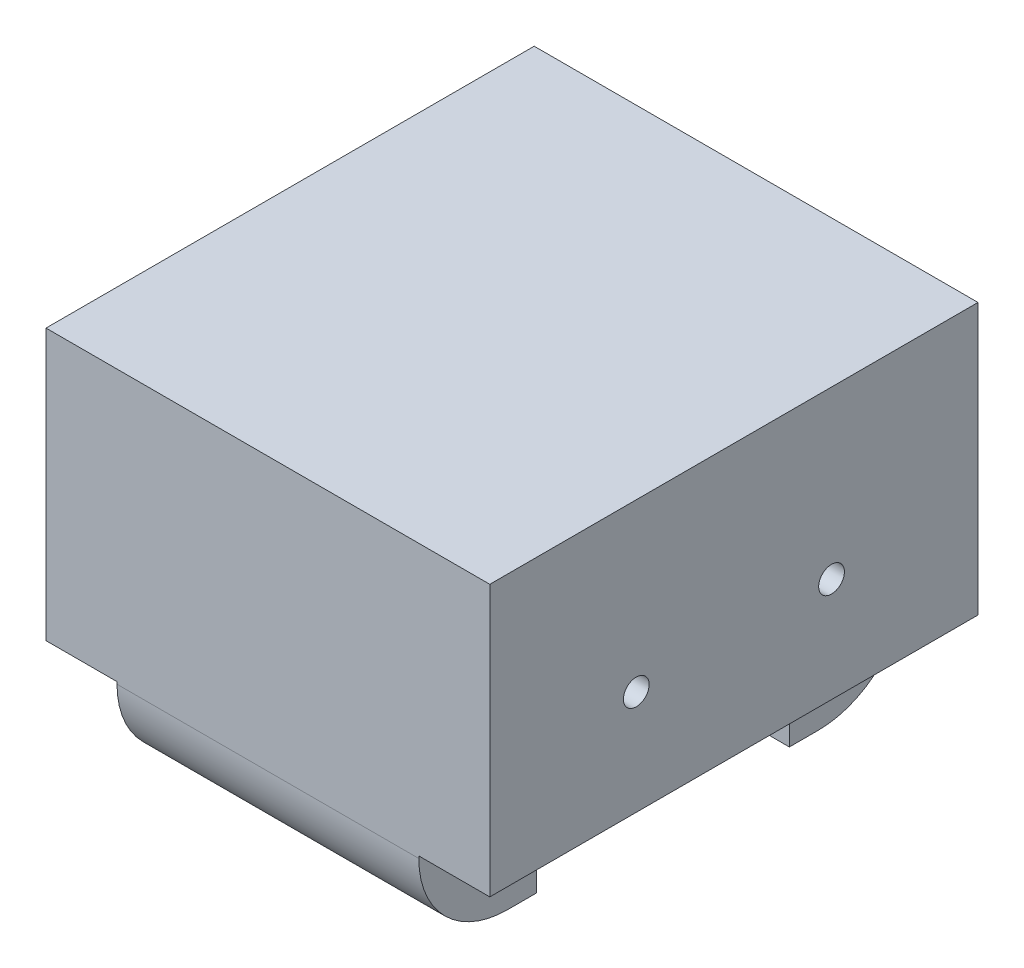
SolidWorks part; units mm, degrees
ref_plane "Front Plane" through (0, 0, 0) normal (0, 0, 1) x (1, 0, 0)
ref_plane "Top Plane" through (0, 0, 0) normal (0, 1, 0) x (1, 0, 0)
ref_plane "Right Plane" through (0, 0, 0) normal (1, 0, 0) x (0, 0, -1)
sketch "Sketch1" plane through (0, 0, 0) normal (0, 0, 1) x (1, 0, 0)
  line L1 (-25, 0) -> (25, 0)
  line L2 (-25, 0) -> (-25, -170)
  line L3 (-25, -170) -> (25, -170)
  line L4 (25, 0) -> (25, -170)
  dimension "D1" = 170
  dimension "D2" = 50
extrude "Boss-Extrude1" add sketch "Sketch1" against normal blind 55
sketch "Sketch2" plane through (0, 0, 0) normal (0, 0, 1) x (1, 0, 0)
  line L0 (25, 0) -> (-25, 0) construction
  line L1 (-17, 0) -> (17, 0)
  line L2 (-17, 0) -> (-17, -27)
  line L3 (-17, -27) -> (17, -27)
  line L4 (17, 0) -> (17, -27)
  line L5 (-25, 0) -> (-25, -170) construction
  dimension "D1" = 8
  dimension "D2" = 34
  dimension "D3" = 27
extrude "Cut-Extrude1" cut sketch "Sketch2" against normal through all
sketch "Sketch3" plane through (25, 0, 0) normal (1, 0, 0) x (0, 0, -1)
  line L0 (0, -170) -> (0, 0) construction
  line L1 (55, -27) -> (0, -27)
  line L2 (55, -27) -> (55, -24)
  line L3 (55, -24) -> (0, -24)
  line L4 (0, -27) -> (0, -24)
  line L5 (55, -170) -> (55, 0) construction
  line L7 (0, 0) -> (10, 0)
  line L8 (0, 0) -> (0, -24)
  line L9 (0, -24) -> (10, -24)
  line L10 (10, 0) -> (10, -24)
  line L11 (55, 0) -> (45, 0)
  line L12 (55, 0) -> (55, -24)
  line L13 (55, -24) -> (45, -24)
  line L14 (45, 0) -> (45, -24)
  circle A0 centre (27.5, -12.75) radius 10.25
  circle A1 centre (27.5, -12.75) radius 4.25
  circle A2 centre (27.5, -12.75) radius 8
  circle A3 centre (27.5, -4.75) radius 1
  circle A4 centre (35.5, -12.75) radius 1
  circle A5 centre (27.5, -20.75) radius 1
  circle A6 centre (19.5, -12.75) radius 1
  point P32 (27.5, -12.75)
  line M7 (0, 0) -> (0, -170)
  line M9 (55, -170) -> (55, 0)
  line M10 (55, 0) -> (0, 0)
  dimension "D2" = 11.25
  dimension "D3" = 27.5
  dimension "D4" = 20.5
  dimension "D7" = 8.5
  dimension "D8" = 16
  dimension "D9" = 4
  dimension "D1" = 3
  dimension "D5" = 10
  dimension "D6" = 10
extrude "Cut-Extrude2" cut sketch "Sketch3" against normal through all contours L14 L3 M10 M9 | L10 L3 M10 M7 | A2 A6 | A2 A6 | A1 | A2 A5 | A2 A5 | A2 A4 | A2 A4 | A2 A3 | A2 A3
sketch "Sketch4" plane through (0, 0, -10) normal (0, 0, 1) x (1, 0, 0)
  line L0 (-25, -24) -> (-17, -24) construction
  line L1 (-17, 0) -> (-19, 0)
  line L2 (-17, 0) -> (-17, -24)
  line L3 (-17, -24) -> (-19, -24)
  line L4 (-19, 0) -> (-19, -24)
  line L5 (0, 0) -> (0, -13.53) construction
  line L6 (19, 0) -> (19, -24)
  line L7 (17, -24) -> (19, -24)
  line L8 (17, 0) -> (17, -24)
  line L9 (17, 0) -> (19, 0)
  dimension "D1" = 2
extrude "Cut-Extrude3" cut sketch "Sketch4" against normal through all
sketch "Sketch5" plane through (25, 0, 0) normal (1, 0, 0) x (0, 0, -1)
  line L1 (10, 0) -> (45, 0)
  line L2 (10, 0) -> (10, -24)
  line L3 (10, -24) -> (45, -24)
  line L4 (45, 0) -> (45, -24)
  line L5 (38.75, -12.75) -> (38.75, -24)
  line L6 (16.25, -12.75) -> (10, -12.75)
  line L7 (16.25, -12.75) -> (16.25, -24)
  line L8 (16.25, -24) -> (10, -24)
  line L9 (10, -12.75) -> (10, -24)
  line L10 (38.75, -12.75) -> (45, -12.75)
  line L11 (38.75, -12.75) -> (38.75, -24)
  line L12 (38.75, -24) -> (45, -24)
  line L13 (45, -12.75) -> (45, -24)
  circle A0 centre (27.5, -12.75) radius 11.25
  line M8 (45, -24) -> (45, 0)
  line M9 (45, 0) -> (10, 0)
  line M10 (10, 0) -> (10, -24)
  dimension "D1" = 22.5
extrude "Cut-Extrude4" cut sketch "Sketch5" against normal through all contours A0 L10 L4 L6 M9 M10 | L7 L6 L2 L3 | L10 L5 L3 M8
sketch "Sketch6" plane through (0, 0, 0) normal (0, 0, 1) x (1, 0, 0)
  line L1 (-19, -24) -> (19, -24)
  line L2 (-19, -24) -> (-19, -34)
  line L3 (-19, -34) -> (19, -34)
  line L4 (19, -24) -> (19, -34)
  dimension "D1" = 10
extrude "Cut-Extrude5" cut sketch "Sketch6" against normal through all
sketch "Sketch8" plane through (25, 0, 0) normal (1, 0, 0) x (0, 0, -1)
  line L0 (55, -170) -> (55, -24) construction
  line L1 (0, -170) -> (0, -24) construction
  line L2 (41.75, -132.5) -> (13.25, -132.5)
  line L3 (27.5, -132.5) -> (27.5, -179)
  line L4 (41.75, -179) -> (13.25, -179)
  line L5 (13.25, -132.5) -> (13.25, -179)
  line L7 (41.75, -132.5) -> (41.75, -179)
  line L11 (27.5, -167.75) -> (55, -167.75)
  line L12 (27.5, -167.75) -> (27.5, -170)
  line L13 (27.5, -170) -> (55, -170)
  line L14 (55, -167.75) -> (55, -170)
  line L16 (27.5, -167.75) -> (0, -167.75)
  line L17 (27.5, -167.75) -> (27.5, -170)
  line L18 (27.5, -170) -> (0, -170)
  line L19 (0, -167.75) -> (0, -170)
  circle A0 centre (27.5, -167.75) radius 10.25
  circle A1 centre (27.5, -12.75) radius 10.25
  line M4 (0, -24) -> (0, -170)
  line M5 (0, -170) -> (55, -170)
  line M6 (55, -170) -> (55, -24)
  dimension "D1" = 27.5
  dimension "D2" = 20.5
  dimension "D3" = 155
  dimension "D4" = 14.25
  dimension "D5" = 11.25
  dimension "D6" = 46.5
  dimension "D7" = 13.25
extrude "Cut-Extrude7" cut sketch "Sketch8" against normal through all contours A0 L3 L2 L5 L16 | A0 L11 L7 L2 L3 | L11 L7 M5 M6 | L5 L16 M4 M5 | A0 L16 L5 M5 | A0 L13 L7 L11 | L3 A0 L16 | L11 A0 L3 | L16 A0 L18 L3 | A0 L11 L3 M5
sketch "Sketch9" plane through (0, 0, 0) normal (0, 0, 1) x (1, 0, 0)
  line L0 (-25, -167.75) -> (25, -167.75) construction
  line L1 (17, -167.75) -> (-17, -167.75)
  line L2 (17, -167.75) -> (17, -132.5)
  line L3 (17, -132.5) -> (-17, -132.5)
  line L4 (-17, -167.75) -> (-17, -132.5)
  line L5 (-25, -132.5) -> (25, -132.5) construction
  line L7 (-25, -24) -> (-25, -167.75) construction
  line L9 (25, -167.75) -> (25, -24) construction
  dimension "D1" = 8
  dimension "D2" = 8
extrude "Cut-Extrude8" cut sketch "Sketch9" against normal through all
sketch "Sketch11" plane through (25, 0, 0) normal (1, 0, 0) x (0, 0, -1)
  line L0 (27.5, -157.5) -> (27.5, -147.5)
  line L2 (27.5, -147.5) -> (55, -147.5)
  line L3 (27.5, -147.5) -> (27.5, -167.75)
  line L4 (27.5, -167.75) -> (55, -167.75)
  line L5 (55, -147.5) -> (55, -167.75)
  line L6 (27.5, -147.5) -> (0, -147.5)
  line L7 (27.5, -147.5) -> (27.5, -167.75)
  line L8 (27.5, -167.75) -> (0, -167.75)
  line L9 (0, -147.5) -> (0, -167.75)
  circle A0 centre (27.5, -167.75) radius 10.25
  arc A1 (38.75, -12.75) -> (16.25, -12.75) centre (27.5, -12.75) ccw construction
  line M1 (0, -167.75) -> (13.25, -167.75)
  line M2 (13.25, -167.75) -> (13.25, -132.5)
  line M4 (41.75, -132.5) -> (41.75, -167.75)
  line M5 (41.75, -167.75) -> (55, -167.75)
  line M6 (55, -167.75) -> (55, -24)
  line M12 (0, -24) -> (0, -167.75)
  dimension "D1" = 155
  dimension "D2" = 20.5
  dimension "D3" = 10
extrude "Cut-Extrude9" cut sketch "Sketch11" against normal through all contours A0 L0 L6 L8 M2 | A0 L4 L2 L0 M4 | L2 M4 M5 M6 | L6 M2 M12 M1
sketch "Sketch12" plane through (25, 0, 0) normal (1, 0, 0) x (0, 0, -1)
  line L1 (13.25, -132.5) -> (41.75, -132.5)
  line L2 (13.25, -132.5) -> (13.25, -147.5)
  line L3 (13.25, -147.5) -> (41.75, -147.5)
  line L4 (41.75, -132.5) -> (41.75, -147.5)
extrude "Boss-Extrude2" add sketch "Sketch12" against normal blind 8
ref_plane "Plane1" through (0, 0, 0) normal (1, 0, 0) x (0, 0, -1)
mirror "Mirror1" about plane through (0, 0, 0) normal (1, 0, 0) of "Boss-Extrude2"
sketch "Sketch14" plane through (0, 0, 0) normal (0, 0, 1) x (1, 0, 0)
  line L0 (17, -148.55) -> (17, -158.75) construction
  line L1 (-17, -132.5) -> (17, -132.5)
  line L2 (-17, -132.5) -> (-17, -147.5)
  line L3 (-17, -147.5) -> (17, -147.5)
  line L4 (17, -132.5) -> (17, -147.5)
  line L5 (-17, -147.5) -> (17, -147.5)
  line L6 (-17, -147.5) -> (-17, -157.75)
  line L7 (-17, -157.75) -> (17, -157.75)
  line L8 (17, -147.5) -> (17, -157.75)
  line M11 (-17, -147.5) -> (-17, -132.5)
  line M12 (-17, -132.5) -> (17, -132.5)
  line M13 (17, -132.5) -> (17, -147.5)
  dimension "D1" = 10.25
extrude "Boss-Extrude3" add sketch "Sketch14" against normal blind 13.25 contours L3 M11 M13 M12 | L8 L3 L6 L7
ref_plane "Plane2" through (0, 0, -27.5) normal (0, 0, 1) x (1, 0, 0)
mirror "Mirror2" about plane through (0, 0, -27.5) normal (0, 0, 1) of "Boss-Extrude3"
sketch "Sketch16" plane through (25, 0, 0) normal (1, 0, 0) x (0, 0, -1)
  line L0 (41.75, -132.5) -> (13.25, -132.5) construction
  line L1 (13.25, -132.5) -> (13.25, -147.5) construction
  circle A1 centre (16.5, -135.75) radius 2.5
  circle A2 centre (16.5, -135.75) radius 4.5
  circle A3 centre (38.5, -135.75) radius 4.5
  dimension "D1" = 3.25
  dimension "D2" = 3.25
  dimension "D3" = 2
extrude "Cut-Extrude13" cut sketch "Sketch16" against normal blind 8 contours A1 | A2 A1 | A3
mirror "Mirror3" about plane through (0, 0, 0) normal (1, 0, 0) of "Cut-Extrude13"
sketch "Sketch17" plane through (25, 0, 0) normal (1, 0, 0) x (0, 0, -1)
  line L0 (55, -147.5) -> (55, -24) construction
  line L1 (38.75, -24) -> (55, -24)
  line L2 (38.75, -24) -> (38.75, -42)
  line L3 (38.75, -42) -> (55, -42)
  line L4 (55, -24) -> (55, -42)
  line L5 (0, -147.5) -> (0, -24) construction
  line L6 (16.25, -24) -> (0, -24)
  line L7 (16.25, -24) -> (16.25, -42)
  line L8 (16.25, -42) -> (0, -42)
  line L9 (0, -24) -> (0, -42)
  dimension "D1" = 18
  dimension "D2" = 18
extrude "Cut-Extrude14" cut sketch "Sketch17" against normal through all
sketch "Sketch18" plane through (25, 0, 0) normal (1, 0, 0) x (0, 0, -1)
  line L9 (0, -147.5) -> (0, -42) construction
  line L18 (16.25, -42) -> (0, -42)
  line L19 (16.25, -42) -> (16.25, -58.25)
  line L20 (16.25, -58.25) -> (0, -58.25)
  line L21 (0, -42) -> (0, -58.25)
  line L22 (55, -147.5) -> (55, -42) construction
  line L23 (38.75, -42) -> (55, -42)
  line L24 (38.75, -42) -> (38.75, -58.25)
  line L25 (38.75, -58.25) -> (55, -58.25)
  line L26 (55, -42) -> (55, -58.25)
  circle A2 centre (16.25, -58.25) radius 16.25
  circle A3 centre (38.75, -58.25) radius 16.25
  line M9 (55, -42) -> (38.75, -42)
  line M13 (16.25, -42) -> (0, -42)
  line M14 (0, -42) -> (0, -147.5)
  line M16 (55, -147.5) -> (55, -42)
  dimension "D1" = 16.25
  dimension "D2" = 16.25
extrude "Cut-Extrude15" cut sketch "Sketch18" against normal through all contours A2 M13 M14 | A3 M16 M9
sketch "Sketch20" plane through (0, 0, -55) normal (0, 0, -1) x (-1, 0, 0)
  line L2 (21, -52) -> (21, -117)
  line L3 (21, -117) -> (-21, -117)
  line L4 (-21, -52) -> (-21, -117)
  line L5 (25, -58.25) -> (25, -147.5) construction
  line L6 (-25, -147.5) -> (-25, -58.25) construction
  line L7 (17, -157.75) -> (-17, -157.75) construction
  line L8 (21, -117) -> (-21, -117)
  line L9 (21, -117) -> (21, -52)
  line L10 (21, -52) -> (-21, -52)
  line L11 (-21, -117) -> (-21, -52)
  line L13 (21, -52) -> (-21, -52)
  line L14 (21, -52) -> (21, -34)
  line L15 (21, -34) -> (-21, -34)
  line L16 (-21, -52) -> (-21, -34)
  line M4 (25, -58.25) -> (-25, -58.25)
  dimension "D1" = 4
  dimension "D2" = 4
  dimension "D3" = 40.75
  dimension "D4" = 65
  dimension "D5" = 83
extrude "Cut-Extrude18" cut sketch "Sketch20" against normal through all contours L2 L10 L4 M4 | L16 L10 L14 L15 | L4 L3 L2 M4
sketch "Sketch22" plane through (-25, 0, 0) normal (-1, 0, 0) x (0, 0, 1)
  circle A0 centre (-38.5, -135.75) radius 4.5
  circle A1 centre (-38.5, -135.75) radius 1.45
  circle A2 centre (-16.5, -135.75) radius 4.5
  circle A3 centre (-16.5, -135.75) radius 1.45
  dimension "D1" = 2.9
extrude "Boss-Extrude4" add sketch "Sketch22" against normal blind 8
mirror "Mirror4" about plane through (0, 0, 0) normal (1, 0, 0) of "Boss-Extrude4"
sketch "Sketch23" plane through (0, 0, -38.75) normal (0, 0, -1) x (-1, 0, 0)
  line L0 (-19, -12.75) -> (-19, -34) construction
  line L1 (-21, -34) -> (-19, -34)
  line L2 (-21, -34) -> (-21, -24)
  line L3 (-21, -24) -> (-19, -24)
  line L4 (-19, -34) -> (-19, -24)
  line L5 (19, -34) -> (19, -12.75) construction
  line L6 (21, -34) -> (19, -34)
  line L7 (21, -34) -> (21, -24)
  line L8 (21, -24) -> (19, -24)
  line L9 (19, -34) -> (19, -24)
  dimension "D1" = 10
  dimension "D2" = 10
extrude "Cut-Extrude19" cut sketch "Sketch23" against normal through all
fillet "Fillet1" radius 10 2 edges at (0, -157.75, 0) (0, -157.75, -55)
sketch "Sketch24" plane through (-25, 0, 0) normal (-1, 0, 0) x (0, 0, 1)
  line L0 (-55, -58.25) -> (-55, -147.5) construction
  line L1 (0, -117) -> (-55, -117)
  line L2 (0, -117) -> (0, -62)
  line L3 (0, -62) -> (-55, -62)
  line L4 (-55, -117) -> (-55, -62)
  dimension "D1" = 55
extrude "Cut-Extrude20" cut sketch "Sketch24" against normal through all
sketch "Sketch25" plane through (-25, 0, 0) normal (-1, 0, 0) x (0, 0, 1)
  line L1 (-79.9471, 6.7325) -> (29.6959, 6.7325)
  line L2 (-79.9471, 6.7325) -> (-79.9471, -75.841)
  line L3 (-79.9471, -75.841) -> (29.6959, -75.841)
  line L4 (29.6959, 6.7325) -> (29.6959, -75.841)
extrude "Cut-Extrude21" cut sketch "Sketch25" against normal through all
